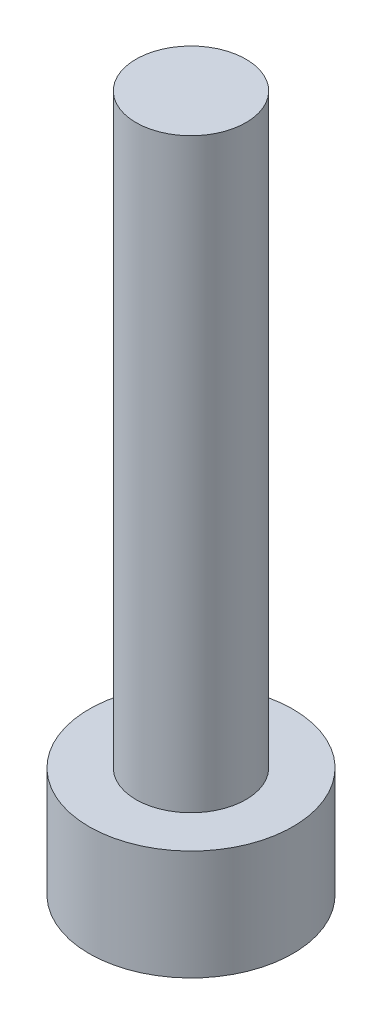
SolidWorks part; units mm, degrees
ref_plane "Front Plane" through (0, 0, 0) normal (0, 0, 1) x (1, 0, 0)
ref_plane "Top Plane" through (0, 0, 0) normal (0, 1, 0) x (1, 0, 0)
ref_plane "Right Plane" through (0, 0, 0) normal (1, 0, 0) x (0, 0, -1)
sketch "Sketch1" plane through (0, 0, 0) normal (0, 1, 0) x (1, 0, 0)
  circle A0 centre (0, 0) radius 2.78
  dimension "D1" = 5.56
extrude "Boss-Extrude1" add sketch "Sketch1" along normal blind 3
sketch "Sketch2" plane through (0, 3, 0) normal (0, 1, 0) x (1, 0, 0)
  circle A0 centre (0, 0) radius 1.5
  dimension "D1" = 3
extrude "Boss-Extrude2" add sketch "Sketch2" along normal blind 16
